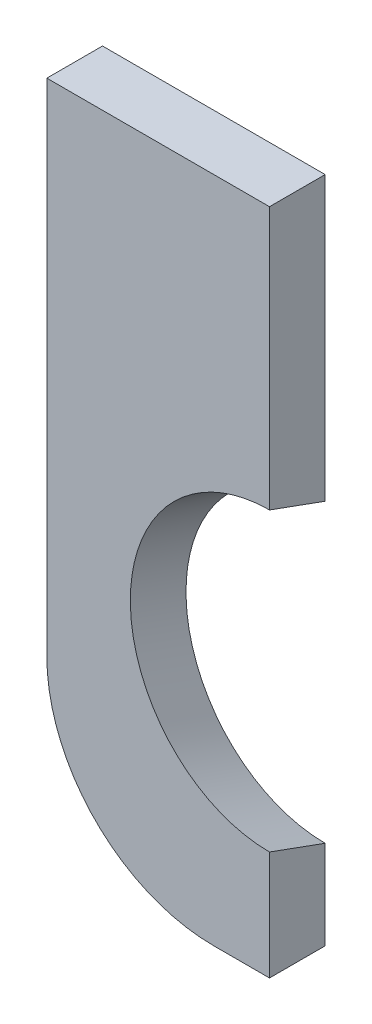
SolidWorks part; units mm, degrees
ref_plane "Plan de face" through (0, 0, 0) normal (0, 0, 1) x (1, 0, 0)
ref_plane "Plan de dessus" through (0, 0, 0) normal (0, 1, 0) x (1, 0, 0)
ref_plane "Plan de droite" through (0, 0, 0) normal (1, 0, 0) x (0, 0, -1)
sketch "Esquisse1" plane through (0, 0, 0) normal (0, 0, 1) x (1, 0, 0)
  line L1 (30, 0) -> (40, 0)
  line L2 (0, 30) -> (0, 120)
  line L3 (0, 120) -> (40, 120)
  line L4 (40, 0) -> (40, 120)
  arc A0 (30, 0) -> (0, 30) centre (30, 30) cw
  point P7 (0, 0)
  dimension "D3" = 30
  dimension "D1" = 40
  dimension "D2" = 120
extrude "Boss.-Extru.1" add sketch "Esquisse1" along normal blind 10
ref_plane "Plan1" through (0, 0, 0) normal (0, -0.342, -0.9397) x (1, 0, 0)
sketch "Esquisse2" plane through (0, 0, 0) normal (0, -0.342, -0.9397) x (1, 0, 0)
  line L0 (40, 0) -> (40, -112.7631) construction
  line L1 (40, 3.4202) -> (40, 0) construction
  line L2 (40, -15) -> (40, -65)
  arc A0 (40, -65) -> (40, -15) centre (40, -40) cw
  point P0 (40, -40)
  dimension "D2" = 25
  dimension "D1" = 40
extrude "Enlèv. mat.-Extru.1" cut sketch "Esquisse2" against normal through all
